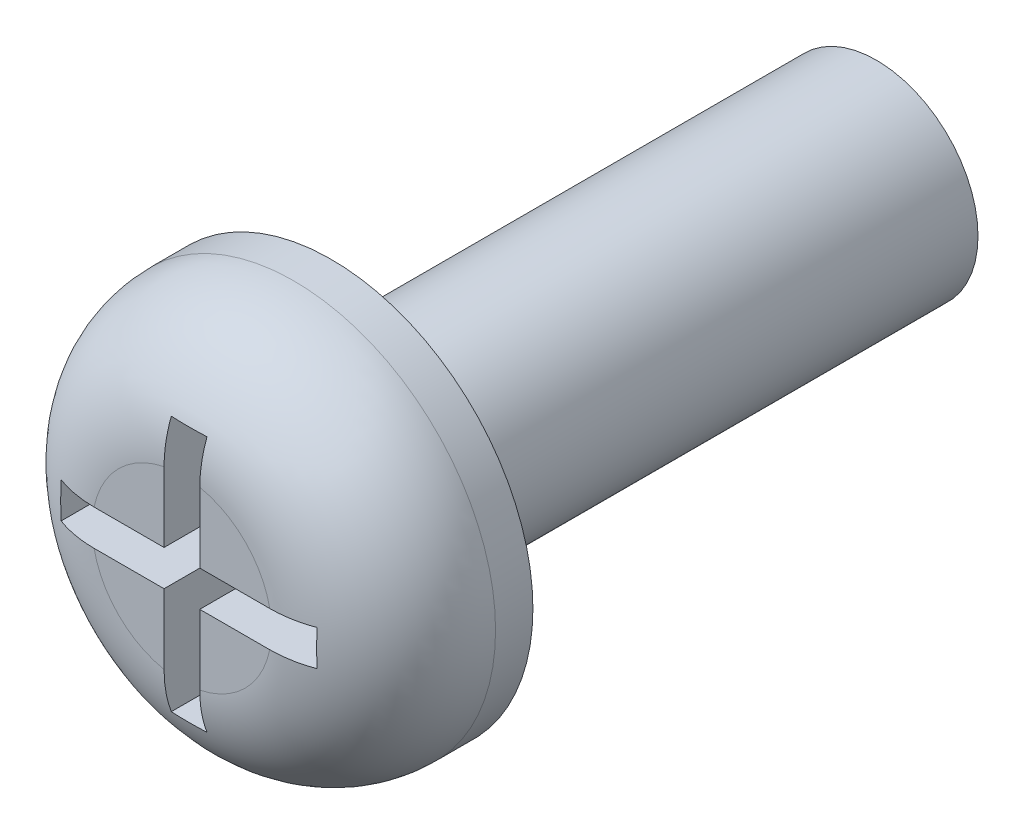
SolidWorks part; units mm, degrees
ref_plane "Front Plane" through (0, 0, 0) normal (0, 0, 1) x (1, 0, 0)
ref_plane "Top Plane" through (0, 0, 0) normal (0, 1, 0) x (1, 0, 0)
ref_plane "Right Plane" through (0, 0, 0) normal (1, 0, 0) x (0, 0, -1)
sketch "Sketch1" plane through (0, 0, 0) normal (0, 0, 1) x (1, 0, 0)
  circle A0 centre (0, 0) radius 1.7272
  dimension "D1" = 3.4544
extrude "Boss-Extrude1" add sketch "Sketch1" along normal blind 9.271
sketch "Sketch2" plane through (0, 0, 9.271) normal (0, 0, 1) x (1, 0, 0)
  circle A0 centre (0, 0) radius 3.429
  dimension "D1" = 6.858
extrude "Boss-Extrude2" add sketch "Sketch2" along normal blind 2.54
fillet "Fillet1" radius 1.905 1 edges at (3.429, 0, 11.811)
sketch "Sketch3" plane through (0, 0, 11.811) normal (0, 0, 1) x (1, 0, 0)
  line L0 (-0.3036, 0.3036) -> (-0.3036, 2.1764)
  line L1 (-2.1764, -0.3036) -> (-0.3036, -0.3036)
  line L2 (-2.1764, -0.3036) -> (-2.1764, 0.3036)
  line L3 (-2.1764, 0.3036) -> (-0.3036, 0.3036)
  line L4 (2.1764, -0.3036) -> (2.1764, 0.3036)
  line L5 (-2.1764, -0.3036) -> (2.1764, 0.3036) construction
  line L6 (-2.1764, 0.3036) -> (2.1764, -0.3036) construction
  line L7 (-0.3036, -2.1764) -> (0.3036, -2.1764)
  line L8 (-0.3036, -2.1764) -> (-0.3036, -0.3036)
  line L9 (-0.3036, 2.1764) -> (0.3036, 2.1764)
  line L10 (0.3036, -2.1764) -> (0.3036, -0.3036)
  line L11 (-0.3036, -2.1764) -> (0.3036, 2.1764) construction
  line L12 (-0.3036, 2.1764) -> (0.3036, -2.1764) construction
  line L14 (0.3036, 0.3036) -> (2.1764, 0.3036)
  line L15 (0.3036, 0.3036) -> (0.3036, 2.1764)
  line L16 (0.3036, -0.3036) -> (2.1764, -0.3036)
  point P0 (0, 0)
  point P6 (0, 0)
  dimension "D1" = 0.6071
  dimension "D2" = 4.3527
extrude "Cut-Extrude1" cut sketch "Sketch3" against normal blind 1.905
